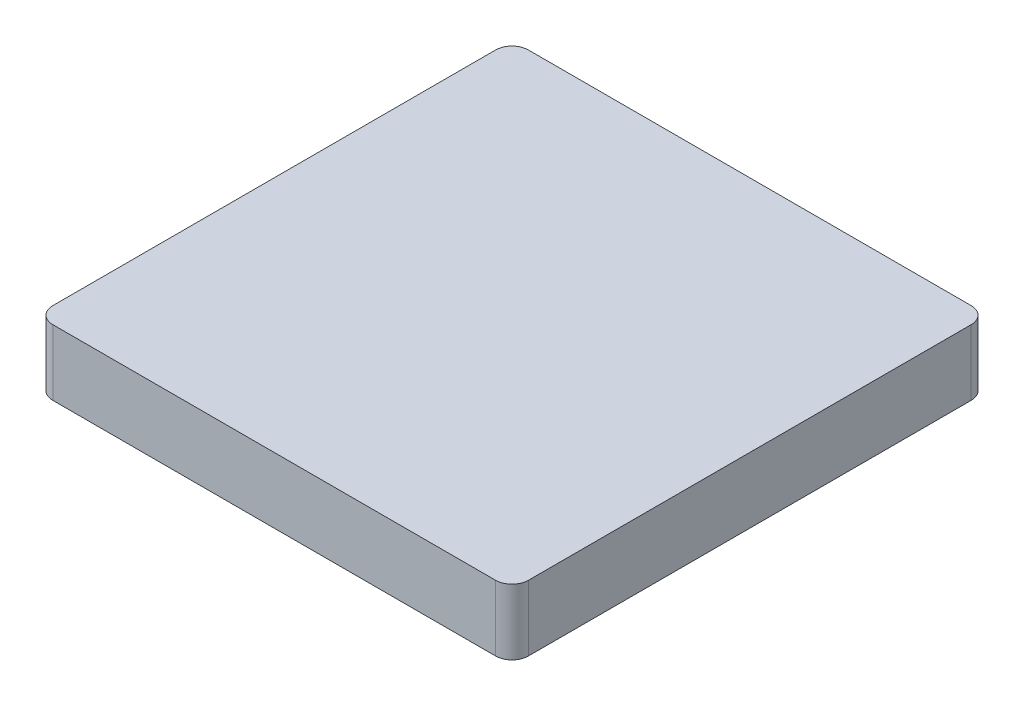
SolidWorks part; units mm, degrees
ref_plane "Front Plane" through (0, 0, 0) normal (0, 0, 1) x (1, 0, 0)
ref_plane "Top Plane" through (0, 0, 0) normal (0, 1, 0) x (1, 0, 0)
ref_plane "Right Plane" through (0, 0, 0) normal (1, 0, 0) x (0, 0, -1)
sketch "Sketch1" plane through (0, 0, 0) normal (0, 1, 0) x (1, 0, 0)
  line L0 (0, -0.935) -> (0, 0.935) construction
  line L1 (-29, 29) -> (29, 29)
  line L2 (-29, 29) -> (-29, -29)
  line L3 (-29, -29) -> (29, -29)
  line L4 (29, 29) -> (29, -29)
  line L5 (-0.935, 0) -> (0.935, 0) construction
  point P4 (0, 29)
  point P8 (29, 0)
  dimension "D1" = 58
  dimension "D2" = 58
extrude "Boss-Extrude1" add sketch "Sketch1" along normal blind 8
fillet "Fillet1" radius 2 4 edges at (-29, 4, -29) (29, 4, -29) (29, 4, 29) (-29, 4, 29)
